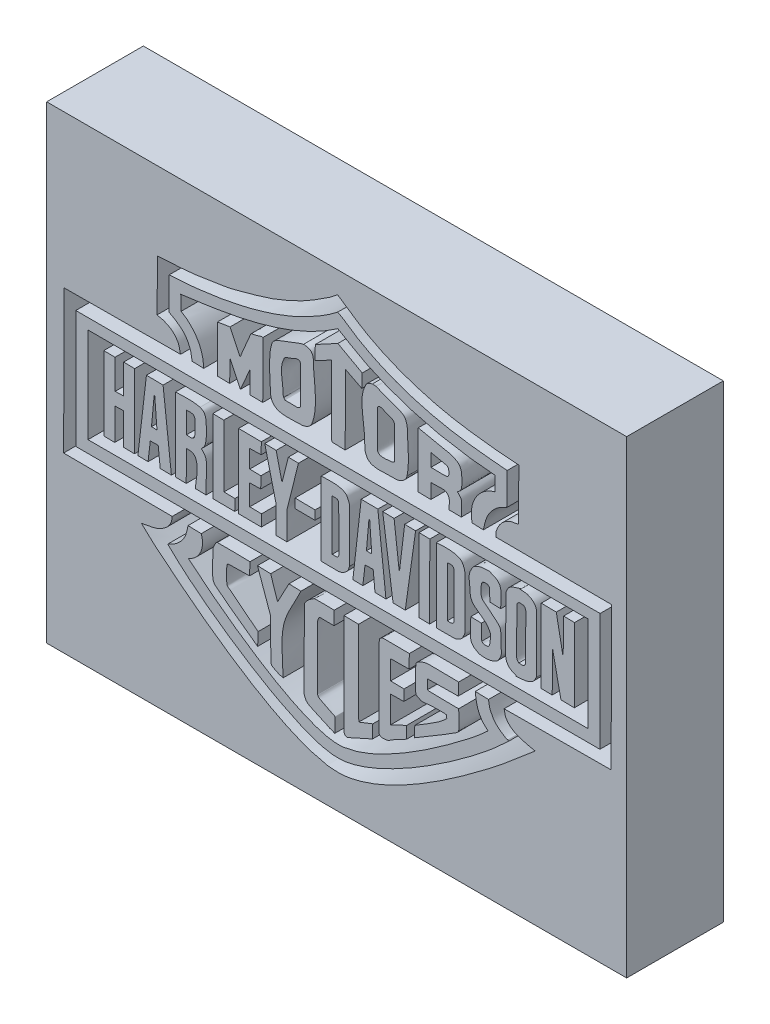
SolidWorks part; units mm, degrees
ref_plane "Front Plane" through (0, 0, 0) normal (0, 0, 1) x (1, 0, 0)
ref_plane "Top Plane" through (0, 0, 0) normal (0, 1, 0) x (1, 0, 0)
ref_plane "Right Plane" through (0, 0, 0) normal (1, 0, 0) x (0, 0, -1)
sketch "Sketch1" plane through (0, 0, 0) normal (0, 0, 1) x (1, 0, 0)
  line L0 (466.6667, 1080) -> (151.6809, 1080) construction
  line L1 (97.7078, 80.7603) -> (97.5818, 70.0923)
  line L2 (92.9198, 65.4723) -> (116.9018, 65.3463)
  line L3 (116.9018, 65.3463) -> (116.7758, 35.6943)
  line L4 (116.7758, 35.6943) -> (94.6418, 35.5683)
  line L5 (25.9718, 35.6943) -> (3.5018, 35.8203)
  line L6 (3.5018, 35.8203) -> (3.6278, 65.4723)
  line L7 (3.6278, 65.4723) -> (27.6938, 65.5983)
  line L8 (22.8218, 70.2183) -> (22.9478, 80.8443)
  line L9 (95.2718, 78.5763) -> (95.1878, 71.8983)
  line L10 (90.3578, 65.4723) -> (88.0478, 65.5563)
  line L11 (92.7938, 73.4943) -> (92.7098, 76.4763)
  line L12 (27.7358, 76.3923) -> (27.8198, 73.3683)
  line L13 (32.4818, 65.4723) -> (30.0878, 65.5563)
  line L14 (25.2578, 71.9823) -> (25.3418, 78.6603)
  line L15 (60.2438, 83.8263) -> (65.2838, 81.0543)
  line L16 (65.2838, 81.0543) -> (65.1998, 78.2403)
  line L17 (65.1998, 78.2403) -> (61.8398, 79.9623)
  line L18 (61.8398, 79.9623) -> (61.7558, 65.4723)
  line L19 (61.7558, 65.4723) -> (58.9838, 65.5563)
  line L20 (58.9838, 65.5563) -> (58.8998, 80.1723)
  line L21 (58.8998, 80.1723) -> (55.4978, 78.3663)
  line L22 (55.4978, 78.3663) -> (55.5818, 81.3063)
  line L23 (55.5818, 81.3063) -> (60.2438, 83.8263)
  line L24 (44.7458, 77.1483) -> (44.7038, 65.4723)
  line L25 (44.7038, 65.4723) -> (42.0998, 65.5143)
  line L26 (42.0998, 65.5143) -> (42.0578, 70.0503)
  line L27 (42.0578, 70.0503) -> (40.0838, 65.5143)
  line L28 (40.0838, 65.5143) -> (37.9418, 69.9663)
  line L29 (37.9418, 69.9663) -> (37.8578, 65.4723)
  line L30 (37.8578, 65.4723) -> (35.2958, 65.5143)
  line L31 (35.2958, 65.5143) -> (35.3378, 75.2163)
  line L32 (35.3378, 75.2163) -> (37.9418, 75.6363)
  line L33 (37.9418, 75.6363) -> (39.9998, 71.3103)
  line L34 (85.7798, 65.4723) -> (83.2178, 65.5143)
  line L35 (79.5218, 68.5383) -> (79.4798, 65.4723)
  line L36 (79.4798, 65.4723) -> (76.8758, 65.5143)
  line L37 (76.8758, 65.5143) -> (76.8758, 77.0223)
  line L38 (6.0218, 62.6163) -> (114.5078, 62.5743)
  line L39 (114.5078, 62.5743) -> (114.4658, 38.2143)
  line L40 (114.4658, 38.2143) -> (6.0218, 38.2563)
  line L41 (6.0218, 38.2563) -> (6.0218, 62.6163)
  line L42 (85.2338, 35.6523) -> (85.1498, 33.0903)
  line L43 (85.1498, 33.0903) -> (78.8078, 33.0063)
  line L44 (78.8078, 33.0063) -> (78.8078, 31.0743)
  line L45 (76.0778, 21.0783) -> (76.1618, 23.3463)
  line L46 (82.7978, 27.8823) -> (82.6718, 28.5123)
  line L47 (29.2478, 35.6943) -> (31.9778, 35.6103)
  line L48 (88.6778, 35.6943) -> (91.4078, 35.6103)
  line L49 (42.0578, 35.6103) -> (41.9738, 33.0483)
  line L50 (41.9738, 33.0483) -> (37.5218, 32.9643)
  line L51 (43.7378, 23.9343) -> (43.6538, 21.2463)
  line L52 (43.6118, 35.6943) -> (46.3418, 35.6103)
  line L53 (46.3418, 35.6103) -> (47.7698, 31.2843)
  line L54 (47.7698, 31.2843) -> (50.1218, 35.6943)
  line L55 (50.1218, 35.6943) -> (52.5998, 35.6103)
  line L56 (59.4878, 35.6523) -> (59.4458, 32.8383)
  line L57 (59.4458, 32.8383) -> (56.7578, 32.8803)
  line L58 (59.6138, 13.6443) -> (58.5638, 14.0643)
  line L59 (58.5638, 14.0643) -> (58.5638, 14.0223)
  line L60 (61.5038, 35.6943) -> (64.5278, 35.6523)
  line L61 (64.5278, 35.6523) -> (64.5698, 18.1383)
  line L62 (64.5698, 18.1383) -> (67.4678, 19.2723)
  line L63 (67.4678, 19.2723) -> (67.4258, 16.5423)
  line L64 (75.0278, 35.6523) -> (74.9858, 32.8383)
  line L65 (74.9858, 32.8383) -> (71.1218, 32.7963)
  line L66 (71.1218, 32.7963) -> (71.1638, 28.8063)
  line L67 (71.1638, 28.8063) -> (73.9358, 28.7643)
  line L68 (73.9358, 28.7643) -> (73.8938, 26.4963)
  line L69 (73.8938, 26.4963) -> (71.1218, 26.4543)
  line L70 (71.1218, 26.4543) -> (71.1638, 20.9523)
  line L71 (71.1638, 20.9523) -> (74.4818, 22.5063)
  line L72 (74.4818, 22.5063) -> (74.4818, 20.0283)
  line L73 (8.5418, 60.3903) -> (112.0298, 60.3483)
  line L74 (112.0298, 60.3483) -> (111.9878, 40.6923)
  line L75 (111.9878, 40.6923) -> (8.5418, 40.7343)
  line L76 (8.5418, 40.7343) -> (8.5418, 60.3903)
  line L77 (93.9278, 53.1243) -> (91.7018, 53.2083)
  line L78 (91.7018, 53.2083) -> (91.6178, 55.8123)
  line L79 (87.7538, 48.6303) -> (89.9378, 48.5463)
  line L80 (89.9378, 48.5463) -> (90.0218, 45.3543)
  line L81 (11.8178, 58.3323) -> (14.1278, 58.2903)
  line L82 (14.1278, 58.2903) -> (14.1698, 52.2003)
  line L83 (14.1698, 52.2003) -> (15.8918, 52.2423)
  line L84 (15.8918, 52.2423) -> (15.9338, 58.3323)
  line L85 (15.9338, 58.3323) -> (18.2018, 58.2903)
  line L86 (18.2018, 58.2903) -> (18.1598, 43.0023)
  line L87 (18.1598, 43.0023) -> (15.8918, 43.0443)
  line L88 (15.8918, 43.0443) -> (15.8498, 49.5963)
  line L89 (15.8498, 49.5963) -> (14.1278, 49.5543)
  line L90 (14.1278, 49.5543) -> (14.0858, 43.0023)
  line L91 (14.0858, 43.0023) -> (11.8178, 43.0443)
  line L92 (11.8178, 43.0443) -> (11.8178, 58.3323)
  line L93 (20.6378, 58.3323) -> (24.0818, 58.2903)
  line L94 (24.0818, 58.2903) -> (25.8038, 43.0023)
  line L95 (25.8038, 43.0023) -> (23.4938, 43.0443)
  line L96 (23.4938, 43.0443) -> (23.0738, 46.9923)
  line L97 (23.0738, 46.9923) -> (21.4358, 46.9503)
  line L98 (21.4358, 46.9503) -> (20.9738, 43.0023)
  line L99 (20.9738, 43.0023) -> (18.8738, 43.0443)
  line L100 (18.8738, 43.0443) -> (20.6378, 58.3323)
  line L101 (32.9858, 43.0443) -> (30.7598, 43.0863)
  line L102 (28.9118, 49.3863) -> (28.8698, 43.0443)
  line L103 (28.8698, 43.0443) -> (26.6438, 43.0863)
  line L104 (26.6438, 43.0863) -> (26.6438, 58.3323)
  line L105 (34.3718, 58.3323) -> (36.6398, 58.2903)
  line L106 (36.6398, 58.2903) -> (36.6818, 45.4383)
  line L107 (36.6818, 45.4383) -> (38.9498, 45.3963)
  line L108 (38.9498, 45.3963) -> (38.9078, 43.0443)
  line L109 (38.9078, 43.0443) -> (34.3718, 43.0863)
  line L110 (34.3718, 43.0863) -> (34.3718, 58.3323)
  line L111 (39.7058, 58.3323) -> (44.4098, 58.2903)
  line L112 (44.4098, 58.2903) -> (44.3678, 55.9383)
  line L113 (44.3678, 55.9383) -> (41.9738, 55.8963)
  line L114 (41.9738, 55.8963) -> (42.0158, 52.2003)
  line L115 (42.0158, 52.2003) -> (44.3258, 52.1583)
  line L116 (44.3258, 52.1583) -> (44.2838, 49.7643)
  line L117 (44.2838, 49.7643) -> (41.9738, 49.7223)
  line L118 (41.9738, 49.7223) -> (42.0158, 45.4383)
  line L119 (42.0158, 45.4383) -> (44.4518, 45.3963)
  line L120 (44.4518, 45.3963) -> (44.4098, 43.0023)
  line L121 (44.4098, 43.0023) -> (39.7058, 43.0443)
  line L122 (39.7058, 43.0443) -> (39.7058, 58.3323)
  line L123 (45.1238, 58.3323) -> (47.4758, 58.2903)
  line L124 (47.4758, 58.2903) -> (48.6938, 53.1243)
  line L125 (48.6938, 53.1243) -> (49.9958, 58.3323)
  line L126 (49.9958, 58.3323) -> (52.0958, 58.2903)
  line L127 (49.7018, 43.0023) -> (47.4758, 43.0443)
  line L128 (56.7998, 43.0863) -> (56.7998, 58.3323)
  line L129 (65.0738, 58.3323) -> (68.5178, 58.2903)
  line L130 (68.5178, 58.2903) -> (70.1978, 43.0023)
  line L131 (70.1978, 43.0023) -> (67.9298, 43.0443)
  line L132 (67.9298, 43.0443) -> (67.5518, 46.9923)
  line L133 (67.5518, 46.9923) -> (65.8718, 46.9503)
  line L134 (65.8718, 46.9503) -> (65.4098, 43.0023)
  line L135 (65.4098, 43.0023) -> (63.3518, 43.0443)
  line L136 (63.3518, 43.0443) -> (65.0738, 58.3323)
  line L137 (69.5258, 58.3323) -> (71.8778, 58.2903)
  line L138 (71.8778, 58.2903) -> (72.9278, 49.4703)
  line L139 (72.9278, 49.4703) -> (73.0118, 49.5123)
  line L140 (73.0118, 49.5123) -> (74.0618, 58.3323)
  line L141 (74.0618, 58.3323) -> (76.3298, 58.2903)
  line L142 (76.3298, 58.2903) -> (74.1878, 43.0023)
  line L143 (74.1878, 43.0023) -> (71.6678, 43.0443)
  line L144 (71.6678, 43.0443) -> (69.5258, 58.3323)
  line L145 (77.0438, 58.3323) -> (79.2698, 58.2903)
  line L146 (79.2698, 58.2903) -> (79.2278, 43.0443)
  line L147 (79.2278, 43.0443) -> (77.0018, 43.0863)
  line L148 (77.0018, 43.0863) -> (77.0438, 58.3323)
  line L149 (80.6138, 43.0443) -> (80.6138, 58.3323)
  line L150 (102.3278, 58.3323) -> (105.4358, 58.2903)
  line L151 (105.4358, 58.2903) -> (106.8638, 50.8983)
  line L152 (106.8638, 50.8983) -> (106.9478, 58.3323)
  line L153 (106.9478, 58.3323) -> (109.2158, 58.2903)
  line L154 (109.2158, 58.2903) -> (109.1738, 43.0023)
  line L155 (109.1738, 43.0023) -> (106.4018, 43.0443)
  line L156 (106.4018, 43.0443) -> (104.6798, 51.3183)
  line L157 (104.6798, 51.3183) -> (104.5958, 43.0023)
  line L158 (104.5958, 43.0023) -> (102.3278, 43.0443)
  line L159 (102.3278, 43.0443) -> (102.3278, 58.3323)
  line L160 (51.3818, 51.6963) -> (55.5398, 51.6543)
  line L161 (55.5398, 51.6543) -> (55.4978, 49.7643)
  line L162 (55.4978, 49.7643) -> (51.3818, 49.8063)
  line L163 (51.3818, 49.8063) -> (51.3818, 51.6963)
  line L164 (82.9238, 45.4803) -> (82.9238, 55.8963)
  line L165 (66.6698, 55.5183) -> (66.8378, 55.4763)
  line L166 (66.8378, 55.4763) -> (67.2578, 49.5963)
  line L167 (67.2578, 49.5963) -> (66.1658, 49.6383)
  line L168 (66.1658, 49.6383) -> (66.6698, 55.5183)
  line L169 (59.0678, 45.4383) -> (59.0678, 55.9383)
  line L170 (28.9118, 51.7803) -> (28.9118, 56.2323)
  line L171 (22.2338, 55.5183) -> (22.3598, 55.4763)
  line L172 (22.3598, 55.4763) -> (22.8218, 49.5963)
  line L173 (22.8218, 49.5963) -> (21.6878, 49.6383)
  line L174 (21.6878, 49.6383) -> (22.2338, 55.5183)
  line L175 (79.5218, 71.2683) -> (79.5218, 73.9143)
  line L177 (0, 0) -> (120, 0)
  line L178 (0, 0) -> (0, 97)
  line L179 (0, 97) -> (120, 97)
  line L180 (120, 0) -> (120, 97)
  line L181 (0, 0) -> (120, 97) construction
  line L182 (0, 97) -> (120, 0) construction
  arc A0 (88.0478, 65.5563) -> (92.7938, 73.4943) centre (94.3898, 67.1523) cw
  arc A1 (31.9778, 35.6103) -> (29.2898, 29.8563) centre (27.7568, 34.0773) cw
  spline S0 degree 3 poles (60.2018, 92.5203) (62.0918, 91.2743) (63.9138, 89.9183) (65.8718, 88.7823) (67.5886, 87.7863) (69.3784, 86.9107) (71.2058, 86.1363) (73.1507, 85.3121) (75.1455, 84.5976) (77.1698, 83.9943) (79.3794, 83.3358) (81.6244, 82.7844) (83.8898, 82.3563) (86.4462, 81.8733) (89.0334, 81.5628) (91.6178, 81.2643) (93.6413, 81.0306) (95.6778, 80.9283) (97.7078, 80.7603) knots 0 0 0 0 1 1 1 2 2 2 3 3 3 4 4 4 5 5 5 6 6 6 6
  spline S1 degree 3 poles (97.5818, 70.0923) (96.9518, 69.9523) (96.2798, 69.9383) (95.6918, 69.6723) (95.0795, 69.3953) (94.5, 68.9991) (94.0538, 68.4963) (93.5963, 67.9806) (93.2879, 67.3358) (93.0458, 66.6903) (92.9025, 66.3081) (92.9618, 65.8783) (92.9198, 65.4723) knots 0 0 0 0 1 1 1 2 2 2 3 3 3 4 4 4 4
  spline S2 degree 3 poles (94.6418, 35.5683) (94.7678, 35.0923) (94.7742, 34.567) (95.0198, 34.1403) (95.3215, 33.6163) (95.7386, 33.1373) (96.2378, 32.7963) (97.6381, 31.84) (99.4139, 31.5738) (101.0678, 31.2003) knots 0 0 0 0 1 1 1 2 2 2 3 3 3 3
  spline S3 degree 3 poles (101.0678, 31.2003) (98.4498, 29.0023) (95.9006, 26.7197) (93.2138, 24.6063) (90.256, 22.2796) (87.2318, 20.0345) (84.1418, 17.8863) (81.6706, 16.1683) (79.1356, 14.5376) (76.5398, 13.0143) (74.4551, 11.7909) (72.309, 10.6662) (70.1138, 9.6543) (68.5365, 8.9272) (66.9048, 8.3076) (65.2418, 7.8063) (63.9695, 7.4228) (62.6589, 7.1328) (61.3358, 7.0083) (60.2618, 6.9072) (59.1793, 7.0804) (58.1018, 7.1343) (58.0576, 7.1365) (58.0186, 7.165) (57.9758, 7.1763) (56.5906, 7.543) (55.1642, 7.7777) (53.8178, 8.2683) (51.8505, 8.9852) (49.9268, 9.8323) (48.0638, 10.7883) (45.6645, 12.0195) (43.3243, 13.3713) (41.0498, 14.8203) (38.1121, 16.6919) (35.2389, 18.6689) (32.4398, 20.7423) (29.1877, 23.1513) (26.035, 25.6936) (22.9058, 28.2603) (21.7489, 29.2093) (20.6938, 30.2763) (19.5878, 31.2843) knots 0 0 0 0 1 1 1 2 2 2 3 3 3 4 4 4 5 5 5 6 6 6 7 7 7 8 8 8 9 9 9 10 10 10 11 11 11 12 12 12 13 13 13 14 14 14 14
  spline S4 degree 3 poles (19.5878, 31.2843) (20.6378, 31.5083) (21.7253, 31.5994) (22.7378, 31.9563) (23.4535, 32.2085) (24.1282, 32.6053) (24.7118, 33.0903) (25.1425, 33.4482) (25.4759, 33.9302) (25.7198, 34.4343) (25.9064, 34.8198) (25.8878, 35.2743) (25.9718, 35.6943) knots 0 0 0 0 1 1 1 2 2 2 3 3 3 4 4 4 4
  spline S5 degree 3 poles (27.6938, 65.5983) (27.5258, 66.2143) (27.4811, 66.8781) (27.1898, 67.4463) (26.8947, 68.0222) (26.4702, 68.5454) (25.9718, 68.9583) (25.4702, 69.3739) (24.8547, 69.6404) (24.2498, 69.8823) (23.7958, 70.0639) (23.2978, 70.1063) (22.8218, 70.2183) knots 0 0 0 0 1 1 1 2 2 2 3 3 3 4 4 4 4
  spline S6 degree 3 poles (22.9478, 80.8443) (25.9587, 81.0857) (29.0048, 81.0671) (31.9778, 81.6003) (34.5538, 82.0623) (37.1975, 82.2398) (39.7058, 82.9863) (42.0154, 83.6737) (44.3682, 84.2291) (46.6358, 85.0443) (48.6599, 85.7719) (50.6413, 86.6301) (52.5578, 87.6063) (54.3871, 88.538) (56.123, 89.6462) (57.8498, 90.7563) (58.6742, 91.2862) (59.4178, 91.9323) (60.2018, 92.5203) knots 0 0 0 0 1 1 1 2 2 2 3 3 3 4 4 4 5 5 5 6 6 6 6
  spline S7 degree 3 poles (60.2018, 89.4123) (61.6798, 88.7405) (62.9215, 87.6366) (64.3178, 86.8083) (65.546, 86.0797) (66.8108, 85.4109) (68.0978, 84.7923) (69.3471, 84.1918) (70.6237, 83.6453) (71.9198, 83.1543) (73.3979, 82.5944) (74.8962, 82.0836) (76.4138, 81.6423) (78.0767, 81.1588) (79.7593, 80.739) (81.4538, 80.3823) (83.2196, 80.0106) (85.0006, 79.7069) (86.7878, 79.4583) (89.604, 79.0666) (92.4414, 78.8459) (95.2718, 78.5763) knots 0 0 0 0 1 1 1 2 2 2 3 3 3 4 4 4 5 5 5 6 6 6 7 7 7 7
  spline S8 degree 3 poles (95.1878, 71.8983) (94.6418, 71.6183) (94.0604, 71.3987) (93.5498, 71.0583) (93.0874, 70.75) (92.668, 70.3736) (92.2898, 69.9663) (91.0031, 68.5806) (90.7226, 67.2502) (90.3578, 65.4723) knots 0 0 0 0 1 1 1 2 2 2 3 3 3 3
  spline S9 degree 3 poles (92.7098, 76.4763) (90.6227, 76.6893) (88.5175, 76.7811) (86.4518, 77.1483) (84.5914, 77.479) (82.7263, 77.7835) (80.8658, 78.1143) (80.835, 78.1198) (80.8122, 78.1485) (80.7818, 78.1563) (79.0195, 78.6107) (77.2522, 79.0459) (75.4898, 79.5003) (75.4595, 79.5081) (75.4355, 79.5322) (75.4058, 79.5423) (73.7972, 80.0923) (72.1845, 80.6303) (70.5758, 81.1803) (70.5462, 81.1904) (70.5205, 81.2097) (70.4918, 81.2223) (69.0505, 81.8538) (67.6066, 82.4794) (66.1658, 83.1123) (66.1085, 83.1375) (66.0528, 83.1663) (65.9978, 83.1963) (64.061, 84.2546) (62.125, 85.318) (60.2438, 86.4723) knots 0 0 0 0 1 1 1 2 2 2 3 3 3 4 4 4 5 5 5 6 6 6 7 7 7 8 8 8 9 9 9 10 10 10 10
  spline S10 degree 3 poles (60.2438, 86.4723) (59.1378, 85.7723) (58.0675, 85.0124) (56.9258, 84.3723) (55.6425, 83.6527) (54.3215, 82.9978) (52.9778, 82.3983) (51.589, 81.7786) (50.1726, 81.2169) (48.7358, 80.7183) (41.7957, 78.3099) (34.9759, 77.3285) (27.7358, 76.3923) knots 0 0 0 0 1 1 1 2 2 2 3 3 3 4 4 4 4
  spline S11 degree 3 poles (27.8198, 73.3683) (28.2818, 73.0463) (28.7832, 72.7745) (29.2058, 72.4023) (29.7261, 71.9441) (30.2108, 71.4395) (30.6338, 70.8903) (31.0133, 70.3976) (31.338, 69.8583) (31.5998, 69.2943) (31.887, 68.6759) (32.1185, 68.0267) (32.2718, 67.3623) (32.4144, 66.7447) (32.4118, 66.1023) (32.4818, 65.4723) knots 0 0 0 0 1 1 1 2 2 2 3 3 3 4 4 4 5 5 5 5
  spline S12 degree 3 poles (30.0878, 65.5563) (29.9898, 66.1443) (29.9005, 66.7338) (29.7938, 67.3203) (29.7882, 67.3511) (29.765, 67.3759) (29.7518, 67.4043) (29.513, 67.9219) (29.3443, 68.4776) (29.0378, 68.9583) (28.1087, 70.4153) (26.7418, 71.2147) (25.2578, 71.9823) knots 0 0 0 0 1 1 1 2 2 2 3 3 3 4 4 4 4
  spline S13 degree 3 poles (25.3418, 78.6603) (27.5128, 78.8306) (29.699, 78.8787) (31.8518, 79.2063) (33.7838, 79.5003) (35.7416, 79.6579) (37.6478, 80.0883) (39.3838, 80.4803) (41.1561, 80.7368) (42.8558, 81.2643) (44.4798, 81.7683) (46.1522, 82.1371) (47.7278, 82.7763) (49.3276, 83.4252) (50.9905, 83.9419) (52.5158, 84.7503) (53.7776, 85.419) (55.0689, 86.0358) (56.2958, 86.7663) (57.6471, 87.5708) (58.9738, 88.4299) (60.2018, 89.4123) knots 0 0 0 0 1 1 1 2 2 2 3 3 3 4 4 4 5 5 5 6 6 6 7 7 7 7
  spline S14 degree 3 poles (46.2998, 68.2863) (46.2904, 70.215) (45.7155, 74.3452) (46.5938, 76.9803) (46.8764, 77.8278) (47.8287, 78.1677) (48.5678, 78.4503) (49.6607, 78.8681) (50.7519, 79.2903) (51.8438, 79.7103) (52.1084, 79.8121) (52.3668, 79.9355) (52.6418, 80.0043) (53.1827, 80.1395) (52.9144, 80.0146) (53.1458, 80.1303) knots 6 6 6 6 7 7 7 8 8 8 9 9 9 10 10 10 11 11 11 11
  spline S15 degree 3 poles (53.1458, 80.1303) (53.7831, 80.0928) (54.4842, 80.0301) (54.8678, 79.4163) (55.0544, 79.1179) (55.1605, 78.8527) (55.1618, 78.4923) (55.1753, 74.7822) (56.2511, 70.882) (55.0778, 67.3623) (54.833, 66.6278) (54.7076, 66.2126) (53.9438, 65.8083) (53.6009, 65.6267) (53.123, 65.4723) (52.7258, 65.4723) (50.0592, 65.4723) (46.3179, 64.5863) (46.2998, 68.2863) knots 0 0 0 0 1 1 1 2 2 2 3 3 3 4 4 4 5 5 5 6 6 6 6
  spline S16 degree 3 poles (74.5658, 67.2363) (74.3787, 66.3006) (73.3529, 65.57) (72.4238, 65.5143) (71.8647, 65.4807) (71.304, 65.4723) (70.7438, 65.4723) (69.6809, 65.4723) (67.0603, 65.0396) (66.2498, 66.4803) (66.0206, 66.8879) (65.8571, 67.2677) (65.8298, 67.7403) (65.7976, 68.2995) (65.7878, 68.8601) (65.7878, 69.4203) (65.7878, 72.5984) (64.4505, 76.1117) (65.8718, 78.9543) (66.0576, 79.3259) (66.0677, 79.5127) (66.4178, 79.7523) (66.7481, 79.9782) (67.0294, 80.0121) (67.3838, 80.1303) knots 8 8 8 8 9 9 9 10 10 10 11 11 11 12 12 12 13 13 13 14 14 14 15 15 15 16 16 16 16
  spline S17 degree 3 poles (67.3838, 80.1303) (67.6358, 80.1163) (67.8888, 80.1147) (68.1398, 80.0883) (68.1595, 80.0862) (68.1631, 80.0526) (68.1818, 80.0463) (68.9089, 79.8039) (69.6136, 79.5215) (70.3238, 79.2483) (71.0544, 78.9673) (71.7821, 78.6805) (72.5078, 78.4083) (73.1908, 78.1522) (73.9506, 77.8979) (74.2718, 77.1483) (74.4484, 76.7363) (74.5994, 76.2944) (74.6078, 75.8463) (74.6594, 73.1028) (75.146, 70.305) (74.6078, 67.6143) (74.583, 67.49) (74.5907, 67.3606) (74.5658, 67.2363) knots 0 0 0 0 1 1 1 2 2 2 3 3 3 4 4 4 5 5 5 6 6 6 7 7 7 8 8 8 8
  spline S18 degree 3 poles (39.9998, 71.3103) (40.1641, 71.4746) (40.2096, 71.7437) (40.2938, 71.9403) (40.3707, 72.1195) (40.427, 72.3071) (40.5038, 72.4863) (40.9018, 73.4147) (41.3189, 74.36) (41.7218, 75.3003) (41.7896, 75.4585) (42.2212, 76.5691) (42.3098, 76.6023) (42.4975, 76.6727) (42.7042, 76.6766) (42.8978, 76.7283) (43.2194, 76.814) (43.5418, 76.8963) (43.8638, 76.9803) (44.172, 77.0607) (44.418, 77.2139) (44.7458, 77.1483) knots 0 0 0 0 1 1 1 2 2 2 3 3 3 4 4 4 5 5 5 6 6 6 7 7 7 7
  spline S19 degree 3 poles (76.8758, 77.0223) (78.4351, 76.7299) (79.9597, 76.3763) (81.4958, 76.0563) (82.3422, 75.88) (83.2252, 75.7977) (84.0158, 75.4683) (84.5709, 75.237) (85.1644, 74.9808) (85.4858, 74.4183) (85.6484, 74.1337) (85.814, 73.8219) (85.8218, 73.4943) (85.8263, 73.3077) (86.1966, 70.8026) (85.5278, 70.0503) (85.3753, 69.8787) (85.1687, 69.7638) (84.9818, 69.6303) knots 0 0 0 0 1 1 1 2 2 2 3 3 3 4 4 4 5 5 5 6 6 6 6
  spline S20 degree 3 poles (84.9818, 69.6303) (85.2842, 69.3279) (85.8095, 68.8502) (85.8218, 68.3703) (85.8466, 67.4045) (85.7938, 66.4383) (85.7798, 65.4723) knots 0 0 0 0 1 1 1 2 2 2 2
  spline S21 degree 3 poles (83.2178, 65.5143) (83.2056, 66.2021) (83.6383, 67.6874) (82.8398, 68.2863) (82.6305, 68.4433) (82.3104, 68.5803) (82.0418, 68.5803) (81.2017, 68.5803) (80.3618, 68.5523) (79.5218, 68.5383) knots 0 0 0 0 1 1 1 2 2 2 3 3 3 3
  spline S22 degree 3 poles (76.4558, 28.9323) (76.4138, 29.1703) (76.3317, 29.4046) (76.3298, 29.6463) (76.3176, 31.2705) (76.1824, 32.9106) (76.4138, 34.5183) (76.4604, 34.8418) (76.8414, 35.033) (77.1278, 35.1903) (77.5041, 35.3969) (78.3837, 35.74) (78.9758, 35.7363) (81.062, 35.7232) (83.1478, 35.6803) (85.2338, 35.6523) knots 0 0 0 0 1 1 1 2 2 2 3 3 3 4 4 4 5 5 5 5
  spline S23 degree 3 poles (78.8078, 31.0743) (78.8778, 31.0323) (78.9363, 30.951) (79.0178, 30.9483) (81.0889, 30.8806) (83.1618, 30.8923) (85.2338, 30.8643) knots 0 0 0 0 1 1 1 2 2 2 2
  spline S24 degree 3 poles (85.2338, 30.8643) (85.2618, 30.4723) (85.3178, 30.0813) (85.3178, 29.6883) (85.3178, 28.7639) (85.4797, 27.8074) (85.2338, 26.9163) (85.1206, 26.5058) (84.6689, 26.2632) (84.3098, 26.0343) (81.6092, 24.3123) (78.8218, 22.7303) (76.0778, 21.0783) knots 0 0 0 0 1 1 1 2 2 2 3 3 3 4 4 4 4
  spline S25 degree 3 poles (76.1618, 23.3463) (78.4006, 24.8184) (80.9032, 25.9877) (82.7978, 27.8823) knots 0 0 0 0 1 1 1 1
  spline S26 degree 3 poles (82.6718, 28.5123) (82.5038, 28.5403) (82.3381, 28.5925) (82.1678, 28.5963) (76.9214, 28.7129) (78.478, 27.8293) (76.4558, 28.9323) knots 0 0 0 0 1 1 1 2 2 2 2
  spline S27 degree 3 poles (29.2898, 29.8563) (30.8858, 28.5543) (32.4465, 27.2077) (34.0778, 25.9503) (35.9896, 24.4768) (37.935, 23.0456) (39.9158, 21.6663) (41.7163, 20.4127) (43.5518, 19.208) (45.4178, 18.0543) (46.9273, 17.121) (48.4662, 16.2326) (50.0378, 15.4083) (51.3246, 14.7334) (52.6429, 14.1152) (53.9858, 13.5603) (54.9843, 13.1478) (56.0102, 12.7966) (57.0518, 12.5103) (57.8488, 12.2913) (58.6648, 12.1231) (59.4878, 12.0483) (60.2413, 11.9798) (61.02, 11.9566) (61.7558, 12.1323) (62.6938, 12.3563) (63.673, 12.4497) (64.5698, 12.8043) (65.8319, 13.3032) (67.1465, 13.6889) (68.3498, 14.3163) (69.9046, 15.1269) (71.4933, 15.8757) (73.0118, 16.7523) (74.9397, 17.8651) (76.8317, 19.0426) (78.6818, 20.2803) (80.8516, 21.7318) (82.9766, 23.2512) (85.0658, 24.8163) (87.2236, 26.4327) (89.3736, 28.0787) (91.3238, 29.9403) knots 0 0 0 0 1 1 1 2 2 2 3 3 3 4 4 4 5 5 5 6 6 6 7 7 7 8 8 8 9 9 9 10 10 10 11 11 11 12 12 12 13 13 13 14 14 14 14
  spline S28 degree 3 poles (91.3238, 29.9403) (90.9318, 30.3183) (90.4779, 30.6411) (90.1478, 31.0743) (89.7984, 31.5329) (89.522, 32.051) (89.3078, 32.5863) (88.9153, 33.5678) (88.783, 34.6425) (88.6778, 35.6943) knots 0 0 0 0 1 1 1 2 2 2 3 3 3 3
  spline S29 degree 3 poles (91.4078, 35.6103) (91.5515, 34.9558) (91.5494, 34.2937) (91.8698, 33.7203) (92.1053, 33.2989) (92.2839, 32.8385) (92.5838, 32.4603) (92.9345, 32.0181) (93.348, 31.6197) (93.8018, 31.2843) (95.8974, 29.7354) (95.0945, 30.8994) (95.5658, 30.1923) knots 0 0 0 0 1 1 1 2 2 2 3 3 3 4 4 4 4
  spline S30 degree 3 poles (95.5658, 30.1923) (94.3898, 29.1283) (93.2531, 28.0192) (92.0378, 27.0003) (90.4796, 25.6939) (88.8798, 24.4361) (87.2498, 23.2203) (85.4626, 21.8872) (83.6429, 20.5963) (81.7898, 19.3563) (79.9596, 18.1315) (78.0994, 16.9494) (76.2038, 15.8283) (73.2345, 14.0721) (70.1643, 12.4541) (66.9638, 11.1663) (65.9617, 10.763) (64.9386, 10.4058) (63.8978, 10.1163) (63.0726, 9.8867) (62.2301, 9.699) (61.3778, 9.6123) (60.57, 9.5301) (59.7537, 9.5988) (58.9418, 9.6123) (58.9105, 9.6128) (58.8884, 9.6476) (58.8578, 9.6543) (57.9618, 9.8503) (57.0298, 9.9234) (56.1698, 10.2423) (54.8947, 10.7151) (53.5683, 11.0701) (52.3478, 11.6703) (50.696, 12.4827) (49.0101, 13.2289) (47.3918, 14.1063) (45.5217, 15.1202) (43.6901, 16.2068) (41.8898, 17.3403) (39.9085, 18.5878) (37.9614, 19.8914) (36.0518, 21.2463) (32.1762, 23.9963) (28.411, 26.9131) (25.0478, 30.2763) knots 0 0 0 0 1 1 1 2 2 2 3 3 3 4 4 4 5 5 5 6 6 6 7 7 7 8 8 8 9 9 9 10 10 10 11 11 11 12 12 12 13 13 13 14 14 14 15 15 15 15
  spline S31 degree 3 poles (25.0478, 30.2763) (25.5658, 30.5563) (26.1188, 30.7796) (26.6018, 31.1163) (27.0492, 31.4281) (27.4613, 31.7975) (27.8198, 32.2083) (28.139, 32.574) (28.414, 32.9858) (28.6178, 33.4263) (28.9473, 34.1384) (29.1033, 34.9231) (29.2478, 35.6943) knots 0 0 0 0 1 1 1 2 2 2 3 3 3 4 4 4 4
  spline S32 degree 3 poles (43.6538, 21.2463) (40.7278, 23.4303) (37.6881, 25.4696) (34.8758, 27.7983) (34.5572, 28.0621) (34.4011, 28.5197) (34.3718, 28.9323) (34.245, 30.7199) (34.3863, 32.5165) (34.4138, 34.3083) (34.4143, 34.3396) (34.4414, 34.3645) (34.4558, 34.3923) (34.6374, 34.7425) (34.7735, 35.1206) (35.0018, 35.4423) (35.0895, 35.5658) (35.2285, 35.6907) (35.3798, 35.6943) (37.6054, 35.7473) (39.8318, 35.6383) (42.0578, 35.6103) knots 0 0 0 0 1 1 1 2 2 2 3 3 3 4 4 4 5 5 5 6 6 6 7 7 7 7
  spline S33 degree 3 poles (37.5218, 32.9643) (37.4378, 32.8243) (37.2787, 32.7073) (37.2698, 32.5443) (37.2075, 31.3979) (37.1231, 30.2328) (37.3118, 29.1003) (37.3591, 28.8169) (37.718, 28.6923) (37.9418, 28.5123) (39.8606, 26.9697) (41.8058, 25.4603) (43.7378, 23.9343) knots 0 0 0 0 1 1 1 2 2 2 3 3 3 4 4 4 4
  spline S34 degree 3 poles (52.5998, 35.6103) (51.3958, 32.9503) (49.5949, 30.4863) (48.9878, 27.6303) (48.3358, 24.5627) (48.9318, 21.3583) (48.9038, 18.2223) knots 0 0 0 0 1 1 1 2 2 2 2
  spline S35 degree 3 poles (48.9038, 18.2223) (48.5398, 18.3483) (48.154, 18.4233) (47.8118, 18.6003) (46.813, 19.1169) (46.401, 19.0996) (46.3838, 19.9863) (46.3311, 22.7159) (46.3414, 25.4465) (46.2998, 28.1763) (46.2994, 28.2076) (46.2684, 28.2308) (46.2578, 28.2603) (45.3723, 30.737) (44.4938, 33.2163) (43.6118, 35.6943) knots 0 0 0 0 1 1 1 2 2 2 3 3 3 4 4 4 5 5 5 5
  spline S36 degree 3 poles (58.5638, 14.0223) (58.3895, 14.1966) (58.1149, 14.2607) (57.8918, 14.3583) (57.0894, 14.7094) (56.2851, 15.0663) (55.4978, 15.4503) (55.0064, 15.69) (53.9263, 16.0844) (53.6078, 16.6683) (53.4451, 16.9666) (53.2718, 17.323) (53.2718, 17.6763) (53.2718, 23.0383) (53.2859, 28.4004) (53.3138, 33.7623) (53.314, 33.7821) (53.3462, 33.787) (53.3558, 33.8043) (53.7501, 34.5139) (54.3343, 35.0296) (55.0358, 35.4423) (55.1977, 35.5375) (55.3521, 35.6905) (55.5398, 35.6943) (56.8557, 35.7206) (58.1718, 35.6663) (59.4878, 35.6523) knots 0 0 0 0 1 1 1 2 2 2 3 3 3 4 4 4 5 5 5 6 6 6 7 7 7 8 8 8 9 9 9 9
  spline S37 degree 3 poles (56.7578, 32.8803) (56.6598, 32.8663) (56.5494, 32.8882) (56.4638, 32.8383) (56.2446, 32.7104) (56.1197, 32.2687) (56.0858, 32.0823) (56.033, 31.7917) (56.0028, 31.4956) (56.0018, 31.2003) (55.9888, 27.0563) (56.0159, 22.9122) (56.0438, 18.7683) (56.044, 18.7485) (56.076, 18.7435) (56.0858, 18.7263) (56.3541, 18.2569) (56.6109, 18.2153) (57.0518, 17.9703) (57.8728, 17.5142) (58.7346, 17.1358) (59.5718, 16.7103) (59.6071, 16.6924) (59.6553, 16.6659) (59.6558, 16.6263) (59.6695, 15.6323) (59.6278, 14.6383) (59.6138, 13.6443) knots 0 0 0 0 1 1 1 2 2 2 3 3 3 4 4 4 5 5 5 6 6 6 7 7 7 8 8 8 9 9 9 9
  spline S38 degree 3 poles (67.4258, 16.5423) (66.1822, 16.0241) (64.9584, 15.4571) (63.7298, 14.9043) (63.3928, 14.7526) (63.0578, 14.5963) (62.7218, 14.4423) (62.5681, 14.3718) (62.426, 14.2639) (62.2598, 14.2323) (61.7478, 14.1348) (61.5065, 14.5773) (61.5038, 15.0303) (61.4628, 21.9182) (61.5038, 28.8063) (61.5038, 35.6943) knots 0 0 0 0 1 1 1 2 2 2 3 3 3 4 4 4 5 5 5 5
  spline S39 degree 3 poles (69.3578, 17.7183) (69.2718, 17.8043) (69.1499, 17.7583) (69.0638, 17.8443) (68.9798, 17.9283) (68.8297, 17.9789) (68.8118, 18.0963) (68.7276, 18.6501) (68.7698, 19.2161) (68.7698, 19.7763) (68.7698, 24.8723) (68.7839, 29.9684) (68.8118, 35.0643) (68.813, 35.2736) (69.3463, 35.6943) (69.5258, 35.6943) (71.3599, 35.6943) (73.1938, 35.6663) (75.0278, 35.6523) knots 0 0 0 0 1 1 1 2 2 2 3 3 3 4 4 4 5 5 5 6 6 6 6
  spline S40 degree 3 poles (74.4818, 20.0283) (69.7105, 17.686) (71.5715, 17.9028) (69.3578, 17.7183) knots 0 0 0 0 1 1 1 1
  spline S41 degree 3 poles (91.3238, 45.0603) (91.4358, 45.2423) (91.6389, 45.3936) (91.6598, 45.6063) (91.7423, 46.4427) (92.0558, 47.4364) (91.5758, 48.1263) (91.3695, 48.4229) (91.2137, 48.7658) (90.9458, 49.0083) (90.1694, 49.7113) (89.2386, 50.2312) (88.4678, 50.9403) (88.1792, 51.2059) (87.9494, 51.5454) (87.7958, 51.9063) (87.6625, 52.2197) (87.6336, 52.5737) (87.6278, 52.9143) (87.6051, 54.2588) (87.0698, 55.7886) (87.7538, 56.9463) (87.92, 57.2274) (88.0205, 57.5621) (88.2578, 57.7863) (88.5406, 58.0534) (88.9057, 58.2273) (89.2658, 58.3743) (89.5991, 58.5103) (89.9563, 58.6097) (90.3158, 58.6263) (91.9779, 58.703) (91.4963, 58.74) (92.0798, 58.4583) (92.4577, 58.2759) (92.8878, 58.1763) (93.2138, 57.9123) (93.4947, 57.685) (93.7259, 57.3718) (93.8438, 57.0303) (94.0003, 56.5773) (94.0015, 56.0815) (94.0118, 55.6023) (94.0296, 54.776) (93.9558, 53.9503) (93.9278, 53.1243) knots 0 0 0 0 1 1 1 2 2 2 3 3 3 4 4 4 5 5 5 6 6 6 7 7 7 8 8 8 9 9 9 10 10 10 11 11 11 12 12 12 13 13 13 14 14 14 15 15 15 15
  spline S42 degree 3 poles (91.6178, 55.8123) (91.4638, 55.9243) (91.3419, 56.1076) (91.1558, 56.1483) (90.8683, 56.2112) (90.5678, 56.1203) (90.2738, 56.1063) knots 0 0 0 0 1 1 1 2 2 2 2
  spline S43 degree 3 poles (90.2738, 56.1063) (90.1618, 55.9243) (89.9597, 55.7729) (89.9378, 55.5603) (89.859, 54.7942) (89.7039, 53.9693) (89.9798, 53.2503) (90.2033, 52.668) (90.8599, 52.3652) (91.3238, 51.9483) (91.9665, 51.3707) (92.6869, 50.8793) (93.2978, 50.2683) (93.5477, 50.0184) (93.8166, 49.7328) (93.8858, 49.3863) (94.0479, 48.5759) (93.9698, 47.7348) (93.9698, 46.9083) (93.9698, 46.0672) (94.2896, 45.1015) (93.8438, 44.3883) (93.6504, 44.0787) (93.5306, 43.7047) (93.2558, 43.4643) (92.9496, 43.1963) (92.5542, 43.0335) (92.1638, 42.9183) (91.6891, 42.7782) (91.1888, 42.7012) (90.6938, 42.7083) (90.1667, 42.7158) (89.5846, 42.7193) (89.1398, 43.0023) (88.8581, 43.1816) (88.5323, 43.3086) (88.2998, 43.5483) (88.0725, 43.7827) (87.8951, 44.0772) (87.7958, 44.3883) (87.6802, 44.7506) (87.6736, 45.142) (87.6698, 45.5223) (87.6596, 46.5586) (87.7258, 47.5943) (87.7538, 48.6303) knots 0 0 0 0 1 1 1 2 2 2 3 3 3 4 4 4 5 5 5 6 6 6 7 7 7 8 8 8 9 9 9 10 10 10 11 11 11 12 12 12 13 13 13 14 14 14 15 15 15 15
  spline S44 degree 3 poles (90.0218, 45.3543) (90.1758, 45.2423) (90.2981, 45.0602) (90.4838, 45.0183) (90.7573, 44.9565) (91.0438, 45.0463) (91.3238, 45.0603) knots 0 0 0 0 1 1 1 2 2 2 2
  spline S45 degree 3 poles (98.6738, 42.7503) (95.9946, 42.5473) (97.6162, 42.613) (96.9938, 42.8763) (96.6586, 43.0181) (96.2875, 43.0926) (95.9858, 43.2963) (95.715, 43.4792) (95.4731, 43.7249) (95.3138, 44.0103) (95.1282, 44.3428) (94.9854, 44.7215) (94.9778, 45.1023) (94.901, 48.9936) (95.0201, 52.8864) (95.0618, 56.7783) (95.0622, 56.8096) (95.0881, 56.8353) (95.1038, 56.8623) (95.2841, 57.1713) (95.3901, 57.5403) (95.6498, 57.7863) (95.9411, 58.0622) (96.3231, 58.2366) (96.6998, 58.3743) (99.4238, 59.3696) (97.363, 58.3489) (97.9178, 58.6263) knots 9 9 9 9 10 10 10 11 11 11 12 12 12 13 13 13 14 14 14 15 15 15 16 16 16 17 17 17 18 18 18 18
  spline S46 degree 3 poles (97.9178, 58.6263) (98.9952, 58.4916) (99.1282, 58.6643) (99.6818, 58.3743) (99.9481, 58.2348) (100.2394, 58.1347) (100.4798, 57.9543) (100.6938, 57.7938) (100.8841, 57.5931) (101.0258, 57.3663) (101.1692, 57.137) (101.3136, 56.8806) (101.3198, 56.6103) (101.412, 52.5934) (101.3475, 48.5742) (101.3198, 44.5563) (101.3194, 44.4937) (101.2677, 44.4422) (101.2358, 44.3883) (101.0856, 44.134) (100.9859, 43.8379) (100.7738, 43.6323) (100.5118, 43.3782) (100.1864, 43.1857) (99.8498, 43.0443) (99.4773, 42.8878) (99.0768, 42.7808) (98.6738, 42.7503) knots 0 0 0 0 1 1 1 2 2 2 3 3 3 4 4 4 5 5 5 6 6 6 7 7 7 8 8 8 9 9 9 9
  spline S47 degree 3 poles (26.6438, 58.3323) (28.142, 58.3182) (29.6728, 58.5622) (31.1378, 58.2483) (31.3179, 58.2097) (31.5038, 58.2029) (31.6838, 58.1643) (31.7032, 58.1601) (31.7081, 58.1312) (31.7258, 58.1223) (31.8772, 58.0466) (32.0365, 57.9879) (32.1878, 57.9123) (32.6815, 57.6655) (32.9689, 56.7781) (32.9858, 56.2743) (33.0226, 55.1829) (33.1302, 54.0807) (32.9858, 52.9983) (32.8341, 51.8599) (32.8397, 51.7582) (32.0198, 50.8563) knots 0 0 0 0 1 1 1 2 2 2 3 3 3 4 4 4 5 5 5 6 6 6 7 7 7 7
  spline S48 degree 3 poles (32.0198, 50.8563) (32.5408, 50.292) (33.0225, 49.7956) (33.0278, 48.9663) (33.0406, 46.9923) (32.9998, 45.0183) (32.9858, 43.0443) knots 0 0 0 0 1 1 1 2 2 2 2
  spline S49 degree 3 poles (30.7598, 43.0863) (30.753, 44.0052) (31.9337, 48.5419) (30.1298, 49.2183) (29.7461, 49.3622) (29.3198, 49.3474) (28.9118, 49.3863) knots 0 0 0 0 1 1 1 2 2 2 2
  spline S50 degree 3 poles (52.0958, 58.2903) (51.7652, 56.8577) (51.3986, 55.4336) (51.0458, 54.0063) (50.7518, 52.8163) (50.4567, 51.6266) (50.1638, 50.4363) (50.0227, 49.8626) (49.7805, 49.304) (49.7438, 48.7143) (49.6257, 46.8139) (49.7158, 44.9063) (49.7018, 43.0023) knots 0 0 0 0 1 1 1 2 2 2 3 3 3 4 4 4 4
  spline S51 degree 3 poles (47.4758, 43.0443) (47.4618, 45.0043) (47.4616, 46.9644) (47.4338, 48.9243) (47.4336, 48.9441) (47.3966, 48.9471) (47.3918, 48.9663) (47.1719, 49.8599) (46.9754, 50.7591) (46.7618, 51.6543) (46.2301, 53.8835) (45.6797, 56.109) (45.1238, 58.3323) knots 0 0 0 0 1 1 1 2 2 2 3 3 3 4 4 4 4
  spline S52 degree 3 poles (56.7998, 58.3323) (57.5184, 58.3237) (61.3429, 58.8235) (62.1758, 57.3243) (62.4345, 56.8588) (62.6777, 56.279) (62.6798, 55.7283) (62.6935, 52.2003) (62.6938, 48.6723) (62.6798, 45.1443) (62.6798, 45.1245) (62.6441, 45.1211) (62.6378, 45.1023) (62.5734, 44.9089) (62.5343, 44.7077) (62.4698, 44.5143) (62.2062, 43.7234) (61.0901, 43.0443) (60.2858, 43.0443) (59.1238, 43.0443) (57.9618, 43.0723) (56.7998, 43.0863) knots 0 0 0 0 1 1 1 2 2 2 3 3 3 4 4 4 5 5 5 6 6 6 7 7 7 7
  spline S53 degree 3 poles (80.6138, 58.3323) (81.1441, 58.3263) (85.2055, 58.8538) (86.0318, 57.3663) (86.2905, 56.9008) (86.5337, 56.321) (86.5358, 55.7703) (86.5495, 52.2143) (86.5498, 48.6583) (86.5358, 45.1023) (86.5354, 44.9926) (86.4318, 44.7681) (86.3678, 44.6403) (86.2922, 44.489) (86.2335, 44.3296) (86.1578, 44.1783) (85.8468, 43.5561) (84.9577, 43.0585) (84.2678, 43.0443) (83.0501, 43.0192) (81.8318, 43.0443) (80.6138, 43.0443) knots 0 0 0 0 1 1 1 2 2 2 3 3 3 4 4 4 5 5 5 6 6 6 7 7 7 7
  spline S54 degree 3 poles (49.0298, 68.5383) (48.963, 68.6645) (48.9467, 68.8155) (48.9458, 68.9583) (48.9326, 71.0864) (48.0781, 73.4388) (49.0298, 75.3423) (49.0775, 75.4377) (49.0908, 75.5518) (49.1558, 75.6363) (49.2345, 75.7386) (49.3413, 75.8185) (49.4498, 75.8883) (49.7035, 76.0514) (50.0092, 76.114) (50.2898, 76.2243) (50.7971, 76.4236) (51.3142, 76.6105) (51.8018, 76.8543) knots 6 6 6 6 7 7 7 8 8 8 9 9 9 10 10 10 11 11 11 12 12 12 12
  spline S55 degree 3 poles (51.8018, 76.8543) (52.24, 76.8105) (52.5158, 76.7648) (52.5158, 76.2243) (52.5158, 73.6903) (52.5017, 71.1562) (52.4738, 68.6223) (52.4706, 68.3239) (51.9269, 68.1635) (51.7178, 68.1603) (50.9338, 68.1484) (50.1495, 68.1748) (49.3658, 68.2023) (49.3461, 68.203) (49.3378, 68.2303) (49.3238, 68.2443) (49.2258, 68.3423) (49.0947, 68.4158) (49.0298, 68.5383) knots 0 0 0 0 1 1 1 2 2 2 3 3 3 4 4 4 5 5 5 6 6 6 6
  spline S56 degree 3 poles (71.9618, 68.5803) (71.9608, 68.4987) (71.8996, 68.4213) (71.8358, 68.3703) (71.6933, 68.2562) (71.44, 68.1603) (71.2478, 68.1603) (70.5471, 68.1603) (68.4338, 67.616) (68.4338, 69.0003) (68.4338, 71.5063) (68.448, 74.0124) (68.4758, 76.5183) (68.4767, 76.5942) (68.7392, 76.797) (68.8538, 76.8543) knots 5 5 5 5 6 6 6 7 7 7 8 8 8 9 9 9 10 10 10 10
  spline S57 degree 3 poles (68.8538, 76.8543) (69.0096, 76.8387) (69.1711, 76.8299) (69.3158, 76.7703) (69.5371, 76.6792) (69.7647, 76.6047) (69.9878, 76.5183) (70.1988, 76.4366) (70.4078, 76.3503) (70.6178, 76.2663) (71.2781, 76.0022) (71.9986, 75.8219) (72.0038, 74.9643) (72.017, 72.8363) (71.9897, 70.7082) (71.9618, 68.5803) knots 0 0 0 0 1 1 1 2 2 2 3 3 3 4 4 4 5 5 5 5
  spline S58 degree 3 poles (97.7078, 45.3123) (97.4565, 45.3458) (97.2466, 45.8993) (97.2458, 46.0683) (97.2323, 49.2603) (97.26, 52.4524) (97.2878, 55.6443) (97.2895, 55.8364) (97.677, 56.1362) (97.8338, 56.1483) (98.1134, 56.1698) (98.3948, 56.1329) (98.6738, 56.1063) (98.7073, 56.1031) (98.8822, 55.9528) (98.9258, 55.9383) knots 5 5 5 5 6 6 6 7 7 7 8 8 8 9 9 9 10 10 10 10
  spline S59 degree 3 poles (98.9258, 55.9383) (98.9456, 55.8789) (98.9914, 55.8301) (99.0098, 55.7703) (99.0608, 55.6048) (99.1344, 55.4395) (99.1358, 55.2663) (99.1624, 52.1164) (99.1217, 48.9662) (99.0938, 45.8163) (99.0937, 45.7965) (99.0607, 45.792) (99.0518, 45.7743) (98.7531, 45.1767) (98.3369, 45.2284) (97.7078, 45.3123) knots 0 0 0 0 1 1 1 2 2 2 3 3 3 4 4 4 5 5 5 5
  spline S60 degree 3 poles (82.9238, 55.8963) (83.3642, 55.8771) (83.9389, 56.0503) (84.1838, 55.5603) (84.2858, 55.3565) (84.3098, 55.1162) (84.3098, 54.8883) (84.3098, 51.9203) (84.2957, 48.9522) (84.2678, 45.9843) (84.2666, 45.847) (84.0841, 45.5857) (83.9318, 45.5223) (83.5707, 45.3718) (83.3366, 45.4545) (82.9238, 45.4803) knots 0 0 0 0 1 1 1 2 2 2 3 3 3 4 4 4 5 5 5 5
  spline S61 degree 3 poles (59.0678, 55.9383) (59.0952, 55.9371) (60.076, 55.9755) (60.2438, 55.7703) (60.3312, 55.6636) (60.4089, 55.5301) (60.4118, 55.3923) (60.4791, 52.285) (60.4538, 49.1763) (60.4538, 46.0683) (60.4538, 45.9104) (60.2816, 45.4968) (60.0758, 45.4803) (59.7406, 45.4535) (59.4038, 45.4523) (59.0678, 45.4383) knots 0 0 0 0 1 1 1 2 2 2 3 3 3 4 4 4 5 5 5 5
  spline S62 degree 3 poles (28.9118, 56.2323) (29.6158, 56.2088) (30.6627, 56.4311) (30.6758, 55.3923) (30.6884, 54.3983) (30.6615, 53.404) (30.6338, 52.4103) (30.6262, 52.1356) (30.2269, 51.7549) (29.9618, 51.7383) (29.6122, 51.7164) (29.2618, 51.7663) (28.9118, 51.7803) knots 0 0 0 0 1 1 1 2 2 2 3 3 3 4 4 4 4
  spline S63 degree 3 poles (79.5218, 73.9143) (80.6704, 73.6846) (81.6913, 73.4828) (82.7978, 73.2423) (82.8172, 73.2381) (82.8258, 73.2143) (82.8398, 73.2003) (82.9238, 73.1163) (83.0329, 73.0514) (83.0918, 72.9483) (83.2197, 72.7245) (83.3123, 71.7408) (83.0918, 71.5203) (83.0078, 71.4363) (82.9573, 71.2862) (82.8398, 71.2683) (82.286, 71.184) (81.72, 71.2263) (81.1598, 71.2263) (80.6137, 71.2263) (80.0678, 71.2543) (79.5218, 71.2683) knots 0 0 0 0 1 1 1 2 2 2 3 3 3 4 4 4 5 5 5 6 6 6 7 7 7 7
  point P250 (61.4858, 52.7783)
  dimension "D1" = 97
  dimension "D2" = 120
extrude "Boss-Extrude2" add sketch "Sketch1" along normal blind 20 contours L177 L180 L179 L178 L8 S6 S0 L1 S1 L2 L3 L4 S2 S3 S4 L5 L6 L7 S5 | S15 S14 S54 S55 | L23 L22 L21 L20 L19 L18 L17 L16 L15 | S17 S16 S56 S57 | S21 L34 S20 S19 L37 L36 L35 L175 S63 | L92 L91 L90 L89 L88 L87 L86 L85 L84 L83 L82 L81 | L100 L99 L98 L97 L96 L95 L94 L93 L173 L174 L171 L172 | S51 L127 S50 L126 L125 L124 L123 | L41 L40 L39 L38 L75 L76 L73 L74 | S52 L128 L169 S61 | L136 L135 L134 L133 L132 L131 L130 L129 L167 L168 L165 L166 | L122 L121 L120 L119 L118 L117 L116 L115 L114 L113 L112 L111 | L110 L109 L108 L107 L106 L105 | L144 L143 L142 L141 L140 L139 L138 L137 | S49 L101 S48 S47 L104 L103 L102 L170 S62 | L148 L147 L146 L145 | S53 L149 L164 S60 | S31 S30 S29 L48 S28 S27 A1 L47 | S44 L80 L79 S43 S42 L78 L77 S41 | S46 S45 S58 S59 | L159 L158 L157 L156 L155 L154 L153 L152 L151 L150 | S33 L50 L49 S32 L51 | S35 S34 L55 L54 L53 L52 | S37 L57 L56 S36 L59 L58 | S38 L63 L62 L61 L60 | S40 L72 L71 L70 L69 L68 L67 L66 L65 L64 S39 | S26 L46 S25 L45 S24 S23 L44 L43 L42 S22 | S18 L33 L32 L31 L30 L29 L28 L27 L26 L25 L24 | S13 L14 S12 L13 S11 L12 S10 S9 L11 A0 L10 S8 L9 S7 | L160 L161 L162 L163
